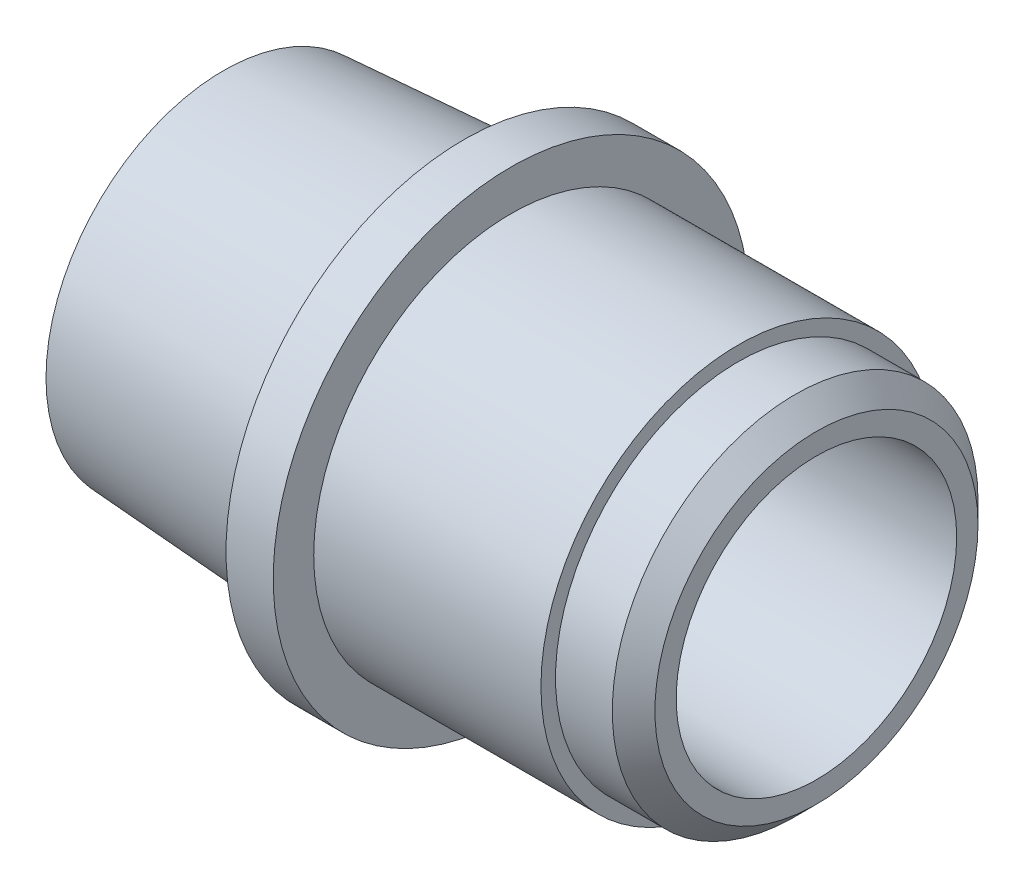
SolidWorks part; units mm, degrees
ref_plane "Front Plane" through (0, 0, 0) normal (0, 0, 1) x (1, 0, 0)
ref_plane "Top Plane" through (0, 0, 0) normal (0, 1, 0) x (1, 0, 0)
ref_plane "Right Plane" through (0, 0, 0) normal (1, 0, 0) x (0, 0, -1)
sketch "Sketch2" plane through (0, 0, 0) normal (0, 0, 1) x (1, 0, 0)
  line L0 (21.209, 8.509) -> (8.5979, 8.509)
  line L1 (8.5979, 0) -> (10.287, 0)
  line L2 (18.415, 1.9685) -> (20.447, 1.9685)
  line L3 (21.209, 2.7305) -> (21.209, 8.509)
  line L4 (21.209, 2.7305) -> (21.209, 8.509)
  line L6 (18.415, 1.9685) -> (18.415, 1.4478)
  line L7 (18.415, 1.4478) -> (10.287, 1.4478)
  line L8 (10.287, 1.4478) -> (10.287, 0)
  line L9 (10.287, 0) -> (8.5979, 0)
  line L10 (8.5979, 0) -> (8.5979, 1.524)
  line L11 (8.5979, 1.524) -> (8.5979, 8.509)
  line L12 (20.447, 1.9685) -> (21.209, 2.7305)
  dimension "D6" = 8.128
  dimension "D7" = 1.6891
revolve "Revolve1" add sketch "Sketch2" angle 360 about L0
sketch "Sketch3" plane through (0, 0, 0) normal (1, 0, 0) x (0, 0, -1)
  circle A0 centre (0, 8.509) radius 6.35
  dimension "D1" = 12.7
ref_plane "Plane3" through (8.636, 0, 0) normal (1, 0, 0) x (0, 0, -1)
sketch "Sketch5" plane through (8.636, 0, 0) normal (1, 0, 0) x (0, 0, -1)
  circle A0 centre (0, 8.509) radius 6.8961
  dimension "D1" = 13.7922
loft "Loft2" add profiles "Sketch3", "Sketch5"
sketch "Sketch7" plane through (21.209, 0, 0) normal (1, 0, 0) x (0, 0, -1)
  circle A3 centre (0, 8.509) radius 5.0165
  circle A4 centre (0, 8.509) radius 5.0165
  dimension "D1" = 0.762
extrude "Extrude2" cut sketch "Sketch7" against normal blind 20.066
